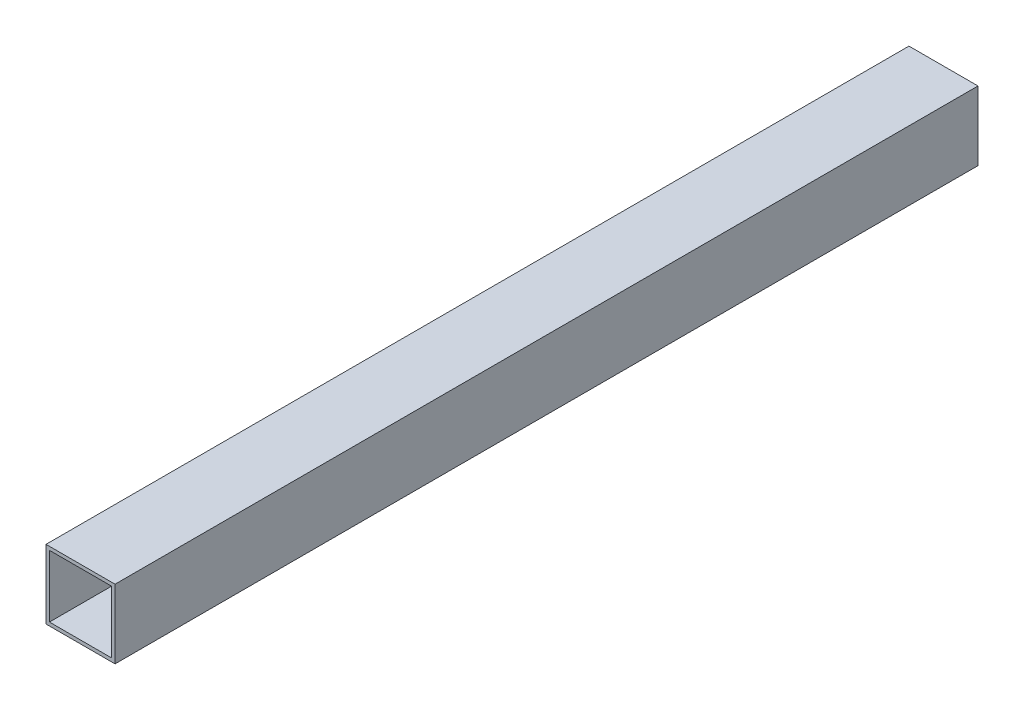
SolidWorks part; units mm, degrees
material "Труба 40х40х2,0 ГОСТ 8639-82 / Ст3сп ГОСТ 13663-86"
ref_plane "Спереди" through (0, 0, 0) normal (0, 0, 1) x (1, 0, 0)
ref_plane "Сверху" through (0, 0, 0) normal (0, 1, 0) x (1, 0, 0)
ref_plane "Справа" through (0, 0, 0) normal (1, 0, 0) x (0, 0, -1)
sketch "Эскиз1" plane through (0, 0, 0) normal (0, 0, 1) x (1, 0, 0)
  line L1 (-20, -20) -> (20, -20)
  line L2 (-20, -20) -> (-20, 20)
  line L3 (-20, 20) -> (20, 20)
  line L4 (20, -20) -> (20, 20)
  line L6 (-18, -18) -> (18, -18)
  line L7 (-18, -18) -> (-18, 18)
  line L8 (-18, 18) -> (18, 18)
  line L9 (18, -18) -> (18, 18)
extrude "Бобышка-Вытянуть1" add sketch "Эскиз1" along normal blind 500
